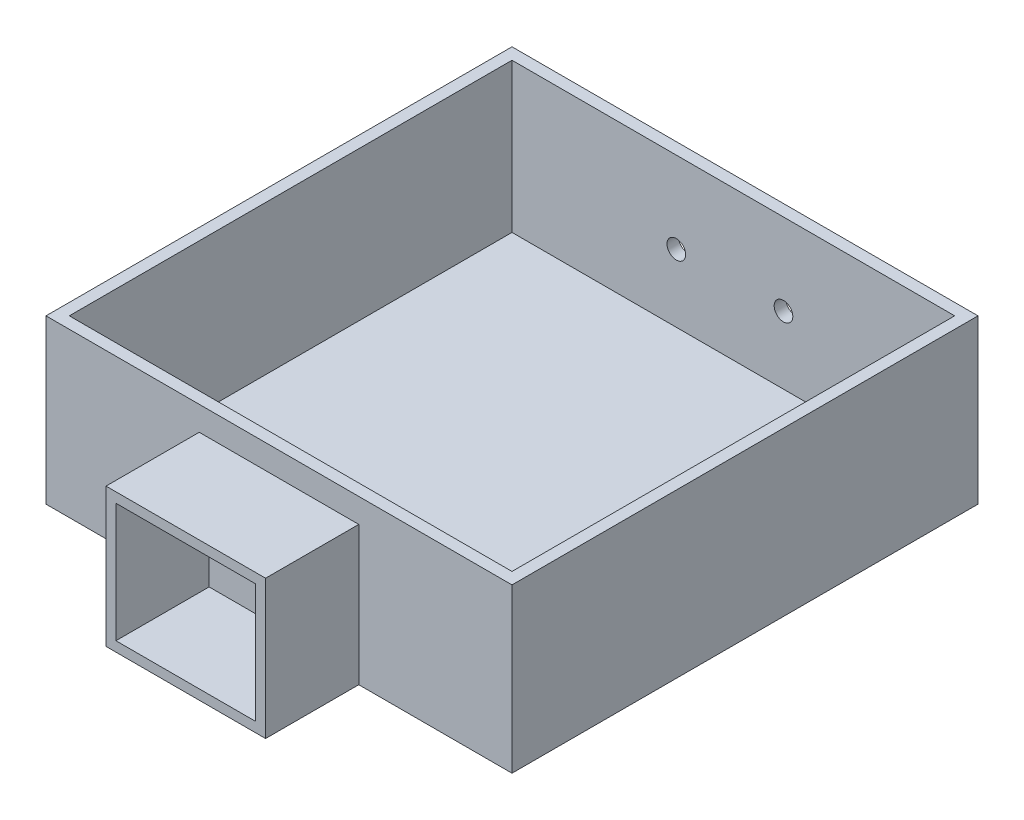
SolidWorks part; units mm, degrees
ref_plane "Спереди" through (0, 0, 0) normal (0, 0, 1) x (1, 0, 0)
ref_plane "Сверху" through (0, 0, 0) normal (0, 1, 0) x (1, 0, 0)
ref_plane "Справа" through (0, 0, 0) normal (1, 0, 0) x (0, 0, -1)
sketch "Эскиз1" plane through (0, 0, 0) normal (0, 1, 0) x (1, 0, 0)
  line L1 (-50, -50) -> (50, -50)
  line L2 (-50, -50) -> (-50, 50)
  line L3 (-50, 50) -> (50, 50)
  line L4 (50, -50) -> (50, 50)
  line L5 (-50, -50) -> (50, 50) construction
  line L6 (-50, 50) -> (50, -50) construction
  point P0 (0, 0)
extrude "Бобышка-Вытянуть1" add sketch "Эскиз1" along normal blind 35
sketch "Эскиз2" plane through (0, 35, 0) normal (0, 1, 0) x (1, 0, 0)
  line L1 (-47.5, -47.5) -> (47.5, -47.5)
  line L2 (-47.5, -47.5) -> (-47.5, 47.5)
  line L3 (-47.5, 47.5) -> (47.5, 47.5)
  line L4 (47.5, -47.5) -> (47.5, 47.5)
  line L5 (-47.5, -47.5) -> (47.5, 47.5) construction
  line L6 (-47.5, 47.5) -> (47.5, -47.5) construction
  point P0 (0, 0)
extrude "Вырез-Вытянуть1" cut sketch "Эскиз2" against normal blind 32
sketch "Эскиз3" plane through (0, 0, 50) normal (0, 0, 1) x (1, 0, 0)
  line L0 (-1050, 17.5) -> (48950, 17.5) construction
  line L2 (0, -1000) -> (0, 49000) construction
  line L3 (-50, 35) -> (-50, 0) construction
  circle A0 centre (0, 17.5) radius 10
  point P8 (-50, 17.5)
extrude "Вырез-Вытянуть2" cut sketch "Эскиз3" against normal blind 32 and the other way through all
sketch "Эскиз4" plane through (0, 0, -50) normal (0, 0, -1) x (-1, 0, 0)
  line L0 (-1050, 17.5) -> (48950, 17.5) construction
  line L1 (-50, 35) -> (-50, 0) construction
  line L2 (0, -1000) -> (0, 49000) construction
  circle A0 centre (-10.7628, 17.5) radius 2
  circle A1 centre (12.2372, 17.5) radius 2
  point P5 (-50, 17.5)
  dimension "D1" = 2
extrude "Вырез-Вытянуть3" cut sketch "Эскиз4" against normal blind 32
sketch "Эскиз5" plane through (0, 0, 50) normal (0, 0, 1) x (1, 0, 0)
  line L0 (-17.118, 5.1996) -> (-17.118, 0)
  line L2 (-17.118, 5.1996) -> (-17.118, 29.8004)
  line L3 (-17.118, 29.8004) -> (17.118, 29.8004)
  line L4 (17.118, 5.1996) -> (17.118, 29.8004)
  line L7 (-50, 0) -> (50, 0) construction
  line L8 (-17.118, 0) -> (17.118, 0)
  line L9 (17.118, 0) -> (17.118, 5.1996)
  point P0 (0, 17.5)
extrude "Бобышка-Вытянуть2" add sketch "Эскиз5" along normal blind 20
sketch "Эскиз6" plane through (0, 0, 50) normal (0, 0, -1) x (-1, 0, 0)
  line L2 (14.9967, 2.1213) -> (14.9967, 27.679)
  line L5 (-14.9967, 2.1213) -> (-14.9967, 27.679)
  line L6 (14.9967, 27.679) -> (-14.9967, 27.679)
  line L7 (14.9967, 2.1213) -> (-14.9967, 2.1213)
extrude "Вырез-Вытянуть4" cut sketch "Эскиз6" against normal through all
